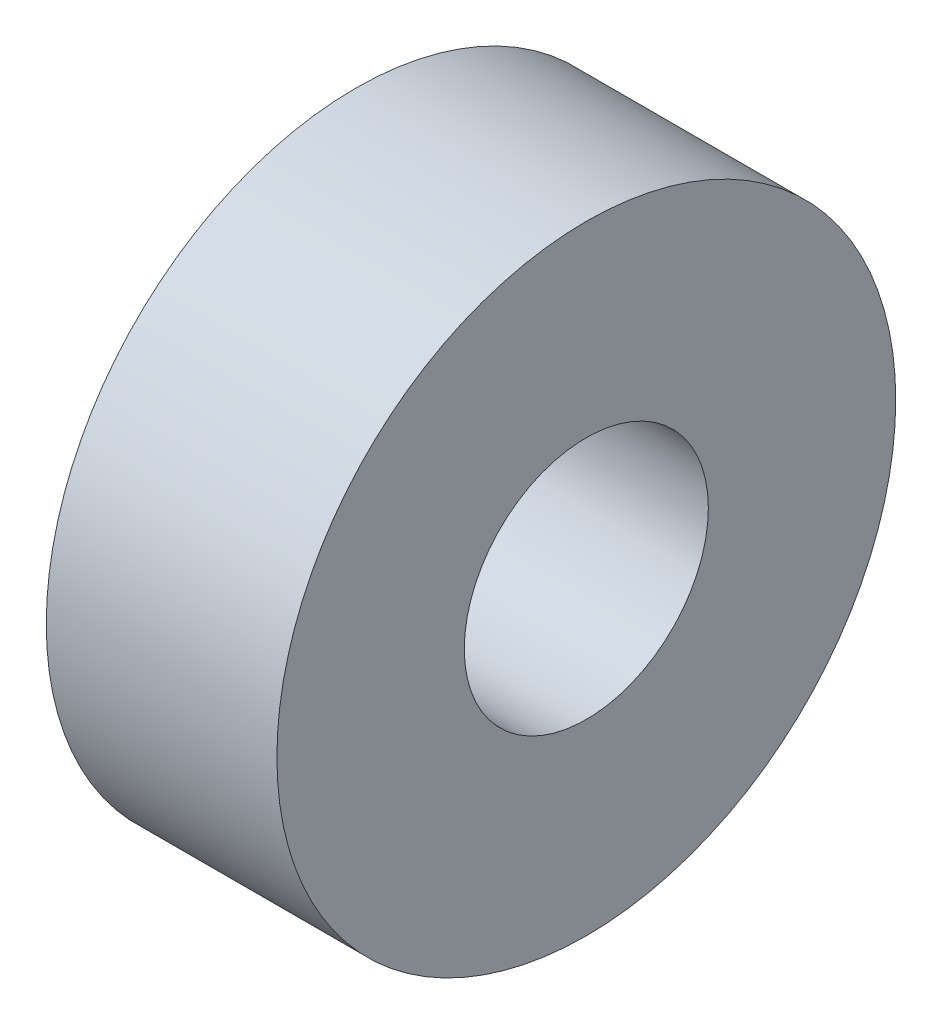
SolidWorks part; units mm, degrees
ref_plane "Alzado" through (0, 0, 0) normal (0, 0, 1) x (1, 0, 0)
ref_plane "Planta" through (0, 0, 0) normal (0, 1, 0) x (1, 0, 0)
ref_plane "Vista lateral" through (0, 0, 0) normal (1, 0, 0) x (0, 0, -1)
sketch "Croquis1" plane through (0, 0, 0) normal (0, 0, 1) x (1, 0, 0)
  line L0 (-5.7122, 0) -> (9.1822, 0) construction
  line L1 (-6, 8.05) -> (0, 8.05)
  line L2 (0, 8.05) -> (0, 3.175)
  line L3 (0, 3.175) -> (-5, 3.175)
  line L4 (-5, 3.175) -> (-5, 4.535)
  line L5 (-5, 4.535) -> (-1.55, 4.535)
  line L6 (-1.55, 4.535) -> (-1.55, 6.85)
  line L7 (-1.55, 6.85) -> (-6, 6.85)
  line L8 (-6, 6.85) -> (-6, 8.05)
  point P6 (-1.55, 7.1567)
  dimension "D1" = 6
  dimension "D2" = 4.45
  dimension "D3" = 5
  dimension "D4" = 3.175
  dimension "D5" = 8.05
  dimension "D6" = 1.2
  dimension "D7" = 1.36
revolve "Revolución1" add sketch "Croquis1" angle 360 about L0
